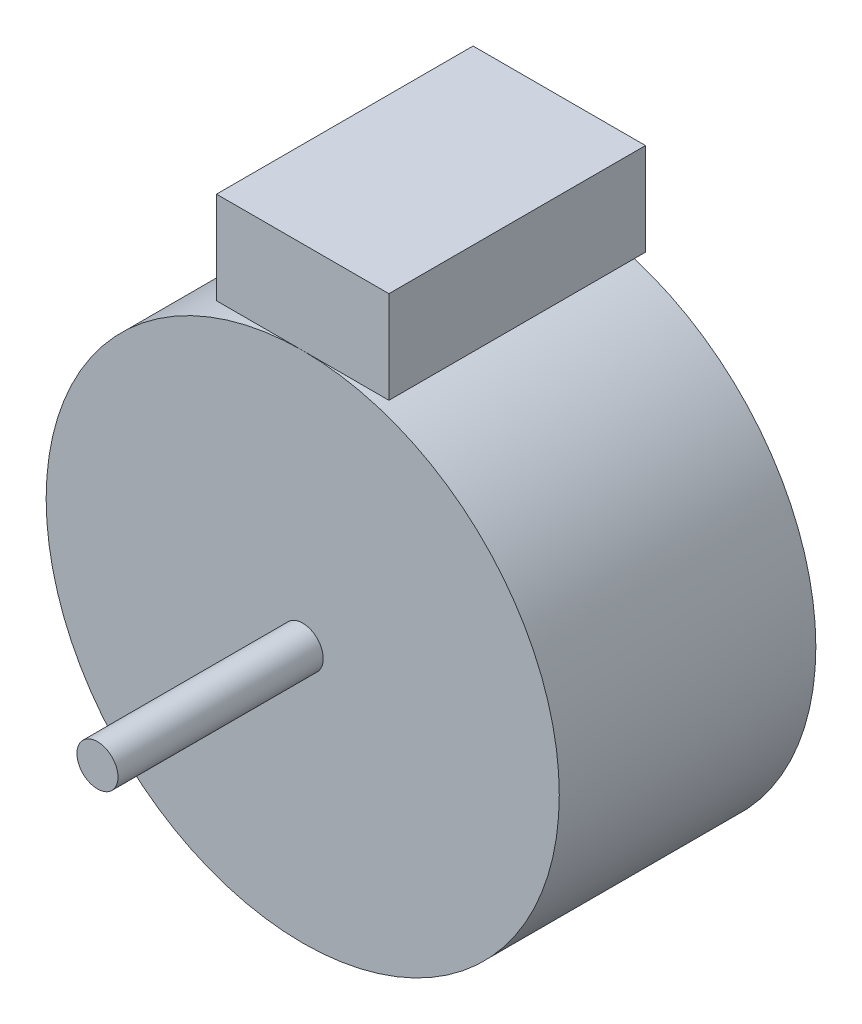
SolidWorks part; units mm, degrees
ref_plane "Alzado" through (0, 0, 0) normal (0, 0, 1) x (1, 0, 0)
ref_plane "Planta" through (0, 0, 0) normal (0, 1, 0) x (1, 0, 0)
ref_plane "Vista lateral" through (0, 0, 0) normal (1, 0, 0) x (0, 0, -1)
sketch "Croquis2" plane through (0, 0, 0) normal (1, 0, 0) x (0, 0, -1)
  line L0 (-38.7864, 0) -> (38.7864, 0) construction
  line L6 (-6.25, 0) -> (6.25, 0)
  line L7 (-6.25, -1) -> (-6.25, -12.5)
  line L8 (-6.25, -12.5) -> (6.25, -12.5)
  line L9 (6.25, 0) -> (6.25, -12.5)
  line L10 (-6.25, 0) -> (-16.25, 0)
  line L11 (-6.25, 0) -> (-6.25, -1) construction
  line L12 (-6.25, -1) -> (-16.25, -1)
  line L13 (-16.25, 0) -> (-16.25, -1)
  point P3 (0, 0)
  point P11 (0, 0)
  dimension "D1" = 12.5
  dimension "D2" = 12.5
  dimension "D3" = 10
  dimension "D4" = 1
revolve "Revolución1" add sketch "Croquis2" angle 360 about L0
sketch "Croquis3" plane through (0, 0, 0) normal (1, 0, 0) x (0, 0, -1)
  line L0 (6.25, -12.5) -> (6.25, 12.5) construction
  line L1 (-6.25, 12.5) -> (6.25, 12.5)
  line L2 (-6.25, 12.5) -> (-6.25, 17)
  line L3 (-6.25, 17) -> (6.25, 17)
  line L4 (6.25, 12.5) -> (6.25, 17)
  dimension "D1" = 4.5
extrude "Saliente-Extruir1" add sketch "Croquis3" along normal mid plane 8.4 separate body
